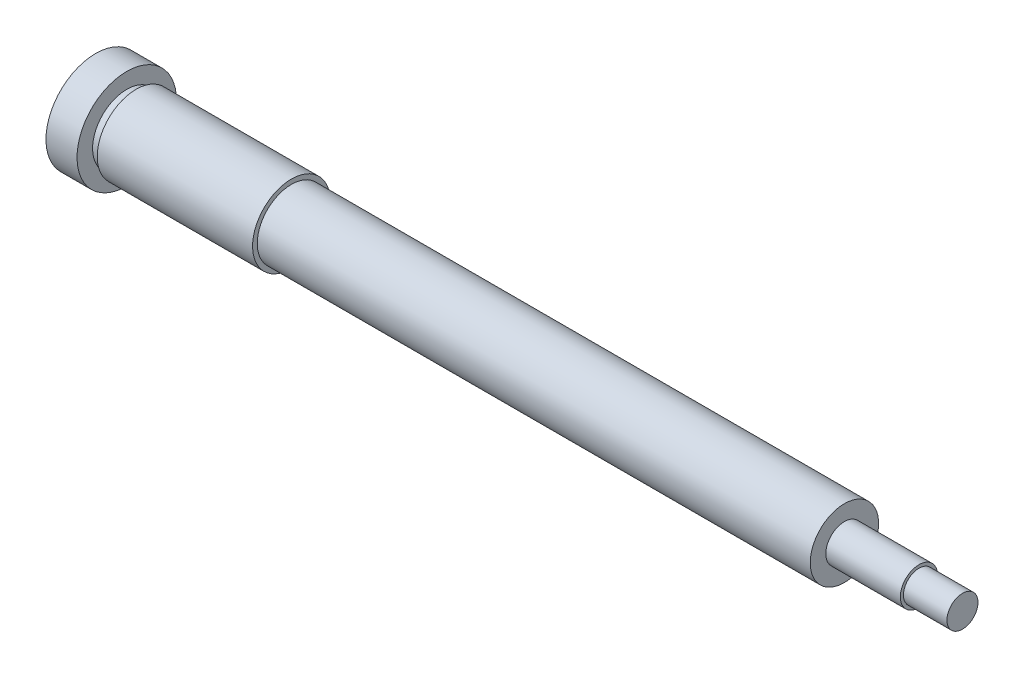
SolidWorks part; units mm, degrees
ref_plane "Piano frontale" through (0, 0, 0) normal (0, 0, 1) x (1, 0, 0)
ref_plane "Piano superiore" through (0, 0, 0) normal (0, 1, 0) x (1, 0, 0)
ref_plane "Piano destro" through (0, 0, 0) normal (1, 0, 0) x (0, 0, -1)
sketch "Schizzo1" plane through (0, 0, 0) normal (0, 0, 1) x (1, 0, 0)
  line L0 (0, 0) -> (-279, 0) construction
  line L1 (-279, 0) -> (-279, 16)
  line L2 (-279, 16) -> (-269, 16)
  line L3 (-269, 16) -> (-269, 11)
  line L4 (-269, 11) -> (-266, 11)
  line L5 (-266, 11) -> (-266, 12.5)
  line L6 (-266, 12.5) -> (-216, 12.5)
  line L7 (-216, 12.5) -> (-216, 11)
  line L8 (-216, 11) -> (-38, 11)
  line L9 (-38, 11) -> (-38, 6)
  line L10 (-38, 6) -> (-14, 6)
  line L11 (-14, 6) -> (-14, 5)
  line L12 (-14, 5) -> (0, 5)
  line L13 (0, 5) -> (0, 0)
  line L14 (0, 0) -> (-279, 0)
  point P10 (0, 0)
  point P16 (-269.3889, 0)
  point P17 (-205.073, 20.9091)
  dimension "D1" = 10
  dimension "D2" = 14
  dimension "D3" = 24
  dimension "D4" = 50
  dimension "D5" = 178
  dimension "D6" = 3
  dimension "D7" = 32
  dimension "D8" = 22
  dimension "D9" = 22
  dimension "D10" = 25
  dimension "D11" = 10
  dimension "D12" = 12
revolve "Rivoluzione1" add sketch "Schizzo1" angle 360 about L0
cosmetic thread "Filettatura cosmetica2" parameters "D2"=23.38
cosmetic thread "Filettatura cosmetica3" parameters "D2"=8.344
